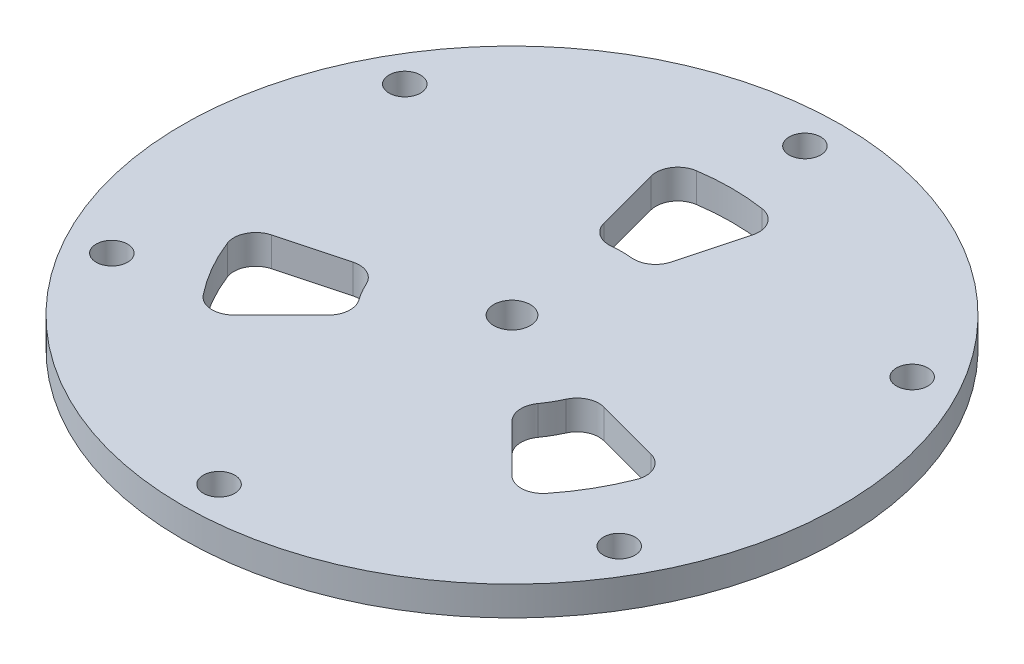
SolidWorks part; units mm, degrees
material "Сосна"
ref_plane "Спереди" through (0, 0, 0) normal (0, 0, 1) x (1, 0, 0)
ref_plane "Сверху" through (0, 0, 0) normal (0, 1, 0) x (1, 0, 0)
ref_plane "Справа" through (0, 0, 0) normal (1, 0, 0) x (0, 0, -1)
sketch "Эскиз1" plane through (0, 0, 0) normal (0, 1, 0) x (1, 0, 0)
  line L0 (0, 0) -> (0, 40) construction
  line L1 (0, 0) -> (-45, 0) construction
  line L2 (-6.9448, 25.9185) -> (-4.5936, 17.1435)
  line L3 (6.9448, 25.9185) -> (4.5936, 17.1435)
  line L4 (18.9737, -18.9737) -> (12.5499, -12.5499)
  line L5 (25.9185, -6.9448) -> (17.1435, -4.5936)
  line L6 (-25.9185, -6.9448) -> (-17.1435, -4.5936)
  line L7 (-18.9737, -18.9737) -> (-12.5499, -12.5499)
  circle A0 centre (0, 0) radius 45
  circle A1 centre (0, 40) radius 2.15
  circle A2 centre (0, -40) radius 2.15
  circle A3 centre (34.641, -20) radius 2.15
  circle A4 centre (-34.641, 20) radius 2.15
  circle A5 centre (-34.641, -20) radius 2.15
  circle A6 centre (34.641, 20) radius 2.15
  circle A7 centre (0, 0) radius 2.5
  circle A8 centre (0, 0) radius 33 construction
  arc A9 (-4.4967, 29.6611) -> (4.4967, 29.6611) centre (0, 0) cw
  arc A10 (-1.4132, 14.9333) -> (1.4132, 14.9333) centre (0, 0) cw
  arc A11 (27.9356, -10.9362) -> (23.4389, -18.7248) centre (0, 0) cw
  arc A12 (13.6392, -6.2428) -> (12.226, -8.6905) centre (0, 0) cw
  arc A13 (-23.4389, -18.7248) -> (-27.9356, -10.9362) centre (0, 0) cw
  arc A14 (-12.226, -8.6905) -> (-13.6392, -6.2428) centre (0, 0) cw
  arc A15 (18.9737, -18.9737) -> (23.4389, -18.7248) centre (21.095, -16.8523) ccw
  arc A16 (27.9356, -10.9362) -> (25.9185, -6.9448) centre (25.1421, -9.8426) ccw
  arc A17 (13.6392, -6.2428) -> (17.1435, -4.5936) centre (16.367, -7.4914) cw
  arc A18 (12.226, -8.6905) -> (12.5499, -12.5499) centre (14.6712, -10.4286) ccw
  arc A19 (-25.9185, -6.9448) -> (-27.9356, -10.9362) centre (-25.1421, -9.8426) ccw
  arc A20 (-23.4389, -18.7248) -> (-18.9737, -18.9737) centre (-21.095, -16.8523) ccw
  arc A21 (-12.5499, -12.5499) -> (-12.226, -8.6905) centre (-14.6712, -10.4286) ccw
  arc A22 (-13.6392, -6.2428) -> (-17.1435, -4.5936) centre (-16.367, -7.4914) ccw
  arc A23 (1.4132, 14.9333) -> (4.5936, 17.1435) centre (1.6958, 17.9199) ccw
  arc A24 (6.9448, 25.9185) -> (4.4967, 29.6611) centre (4.0471, 26.695) ccw
  arc A25 (-6.9448, 25.9185) -> (-4.4967, 29.6611) centre (-4.0471, 26.695) cw
  arc A26 (-4.5936, 17.1435) -> (-1.4132, 14.9333) centre (-1.6958, 17.9199) ccw
  point P18 (0, 0)
  point P21 (0, 30)
  point P34 (0, 0)
  dimension "D2" = 4.3
  dimension "D3" = 90
  dimension "D5" = 5
  dimension "D6" = 66
  dimension "D7" = 15
  dimension "D8" = 30
  dimension "D11" = 3
  dimension "D1" = 40
  dimension "D9" = 30
  dimension "D4" = 3
  dimension "D10" = 3
extrude "Бобышка-Вытянуть1" add sketch "Эскиз1" along normal mid plane 4
